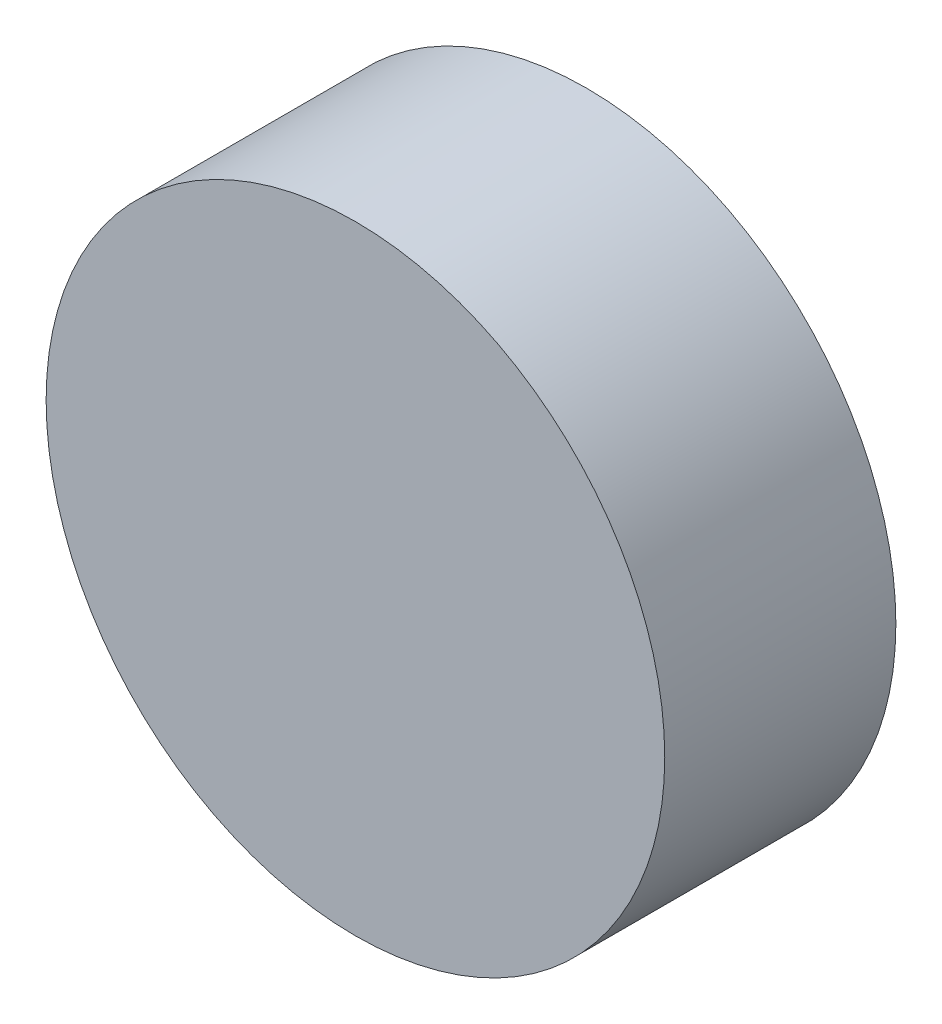
SolidWorks part; units mm, degrees
ref_plane "Front Plane" through (0, 0, 0) normal (0, 0, 1) x (1, 0, 0)
ref_plane "Top Plane" through (0, 0, 0) normal (0, 1, 0) x (1, 0, 0)
ref_plane "Right Plane" through (0, 0, 0) normal (1, 0, 0) x (0, 0, -1)
sketch "Sketch1" plane through (0, 0, 0) normal (0, 0, 1) x (1, 0, 0)
  circle A1 centre (0, 0) radius 8.03
  dimension "D1" = 16.06
extrude "Boss-Extrude1" add sketch "Sketch1" along normal blind 6
equation "\"Outer\"= 8.03"
equation "\"Depth\"= 6"
equation "\"D1@Sketch1\"=\"Outer\"*2"
equation "\"D1@Boss-Extrude1\"=\"Depth\""
